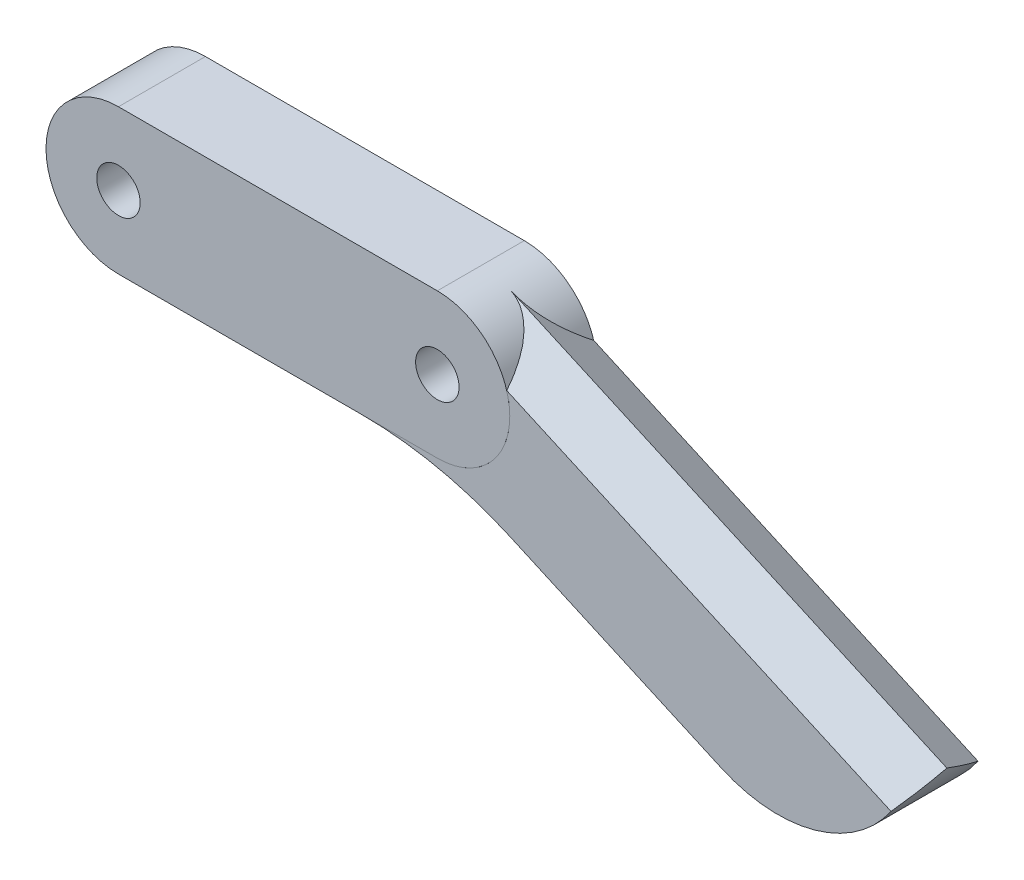
SolidWorks part; units mm, degrees
material "普通碳钢"
ref_plane "前视" through (0, 0, 0) normal (0, 0, 1) x (1, 0, 0)
ref_plane "上视" through (0, 0, 0) normal (0, 1, 0) x (1, 0, 0)
ref_plane "右视" through (0, 0, 0) normal (1, 0, 0) x (0, 0, -1)
sketch "草图1" plane through (0, 0, 0) normal (0, 0, 1) x (1, 0, 0)
  line L0 (-11, 0) -> (11, 0) construction
  line L1 (-11, 5) -> (11, 5)
  line L2 (-11, -5) -> (11, -5)
  arc A0 (-11, 5) -> (-11, -5) centre (-11, 0) ccw
  arc A1 (11, -5) -> (11, 5) centre (11, 0) ccw
  circle A2 centre (-11, 0) radius 1.5
  circle A3 centre (11, 0) radius 1.5
  point P2 (0, 0)
  dimension "D3" = 3
  dimension "D1" = 10
  dimension "D2" = 22
extrude "凸台-拉伸1" add sketch "草图1" along normal blind 6 contours L1 A1 L2 A0 | A2 | A3
sketch "草图2" plane through (0, 0, 6) normal (0, 0, 1) x (1, 0, 0)
  line L1 (30.6027, -13.7199) -> (16.0324, -7.1877)
  line L2 (-11, -5) -> (11, -5) construction
  line L4 (34.9453, -5.2557) -> (43.1577, -8.9375)
  line L6 (5.8051, -5) -> (11, -5)
  line L7 (43.1577, -8.9375) -> (32.6654, -32.341) construction
  line L8 (43.1577, -8.9375) -> (13.0455, 4.5625) construction
  line L9 (0.4545, 25.5498) -> (-11, 0) construction
  line L10 (34.9453, -5.2557) -> (13.0455, 4.5625)
  line L11 (35.1811, -10.8409) -> (36.5498, -11.4545) construction
  arc A0 (11, -5) -> (11, 5) centre (11, 0) ccw construction
  arc A1 (16.0324, -7.1877) -> (5.8051, -5) centre (5.8051, -30) ccw
  arc A2 (11, -5) -> (13.0455, 4.5625) centre (11, 0) ccw
  arc A3 (43.1577, -8.9375) -> (30.6027, -13.7199) centre (34.4891, -5.0512) cw
  circle A5 centre (-11, 0) radius 1.5 construction
  circle A6 centre (0.4545, 25.5498) radius 1.5 construction
  dimension "D5" = 9
  dimension "D6" = 24
  dimension "D8" = 28
  dimension "D9" = 3
  dimension "D10" = 25
  dimension "D3" = 28
  dimension "D4" = 9.5
  dimension "D7" = 33
extrude "凸台-拉伸2" add sketch "草图2" against normal blind 6 separate body
sketch "草图3" plane through (3.8864, 8.6687, 0) normal (0.4091, 0.9125, 0) x (0.9125, -0.4091, 0)
  line L0 (10.0374, -3) -> (43.0374, -3)
  line L1 (10.0374, 0) -> (10.0374, -6) construction
  line L2 (43.0374, 0) -> (43.0374, -6) construction
ref_plane "基准面1" through (2.3833, 5.3162, -3.3636) normal (0.3543, 0.7902, -0.5) x (0.9125, -0.4091, 0)
other "使用曲面切除1"
ref_plane "基准面2" through (3.4462, 7.6869, 4.8636) normal (0.3543, 0.7902, 0.5) x (0.9125, -0.4091, 0)
other "使用曲面切除2"
